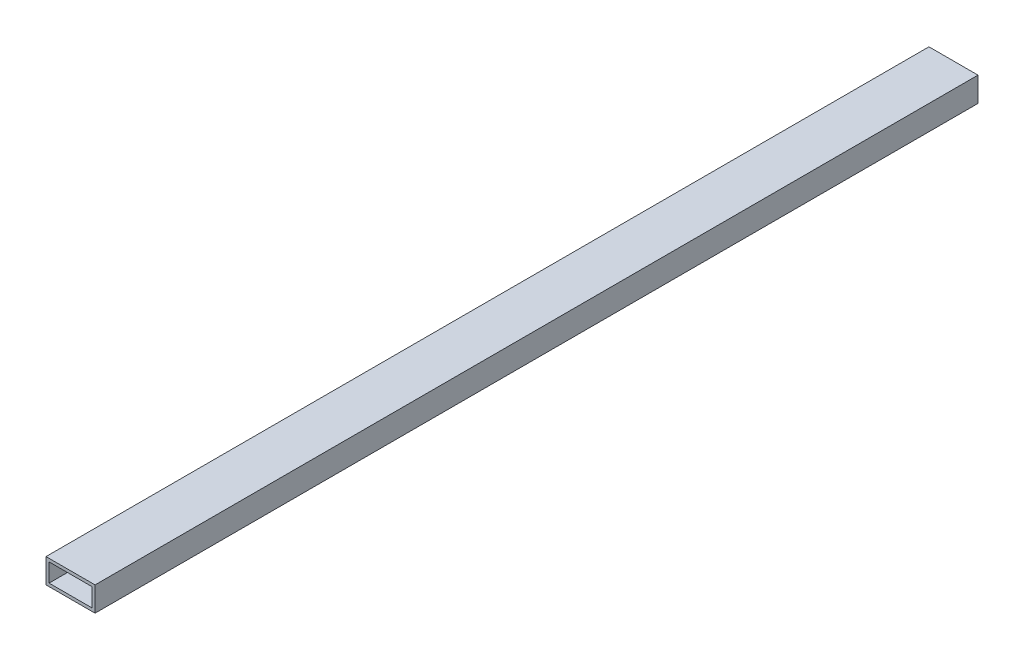
SolidWorks part; units mm, degrees
ref_plane "Front Plane" through (0, 0, 0) normal (0, 0, 1) x (1, 0, 0)
ref_plane "Top Plane" through (0, 0, 0) normal (0, 1, 0) x (1, 0, 0)
ref_plane "Right Plane" through (0, 0, 0) normal (1, 0, 0) x (0, 0, -1)
sketch "Sketch1" plane through (0, 0, 0) normal (0, 0, 1) x (1, 0, 0)
  line L0 (-22.225, 9.525) -> (22.225, 9.525)
  line L2 (-25.4, 12.7) -> (25.4, 12.7)
  line L3 (-25.4, 12.7) -> (-25.4, -12.7)
  line L4 (-25.4, -12.7) -> (25.4, -12.7)
  line L5 (25.4, 12.7) -> (25.4, -12.7)
  line L10 (22.225, 9.525) -> (22.225, -9.525)
  line L11 (-22.225, -9.525) -> (22.225, -9.525)
  line L12 (-22.225, 9.525) -> (-22.225, -9.525)
  point P12 (0, 12.7)
  point P14 (25.4, 0)
  dimension "Wall Thickness" = 3.175
  dimension "Outside Width" = 50.8
  dimension "Outside Height" = 25.4
  dimension "Inside Height" = 19.05
  dimension "Inside Width" = 44.45
sketch "Sketch2" plane through (0, 0, 0) normal (1, 0, 0) x (0, 0, -1)
  line L0 (457.2, 0) -> (-457.2, 0)
  point P4 (0, 0)
  point P7 (-457.2, 0)
  point P10 (457.2, 0)
  dimension "Length" = 914.4
sketch "Sketch3" plane through (0, 0, 0) normal (0, 0, 1) x (1, 0, 0)
  line L21 (25.4, 12.7) -> (-25.4, 12.7)
  line L22 (25.4, -12.7) -> (25.4, 12.7)
  line L23 (-25.4, -12.7) -> (25.4, -12.7)
  line L24 (-25.4, 12.7) -> (-25.4, -12.7)
  line L25 (25.4, 12.7) -> (-25.4, 12.7)
  line L26 (25.4, -12.7) -> (25.4, 12.7)
  line L27 (-25.4, -12.7) -> (25.4, -12.7)
  line L28 (-25.4, 12.7) -> (-25.4, -12.7)
  line L29 (22.225, 9.525) -> (-22.225, 9.525)
  line L30 (22.225, -9.525) -> (22.225, 9.525)
  line L31 (-22.225, -9.525) -> (22.225, -9.525)
  line L32 (-22.225, 9.525) -> (-22.225, -9.525)
  line L33 (22.225, 9.525) -> (-22.225, 9.525)
  line L34 (22.225, -9.525) -> (22.225, 9.525)
  line L35 (-22.225, -9.525) -> (22.225, -9.525)
  line L36 (-22.225, 9.525) -> (-22.225, -9.525)
  dimension "D1" = 0
  dimension "D2" = 0
extrude "Boss-Extrude1" add sketch "Sketch3" along normal up to vertex (457.2 mm away) and the other way up to vertex (457.2 mm away) up to point (0, 0, 457.2) other way up to point (0, 0, -457.2)
sketch "Drawing Reference" plane through (0, 0, 0) normal (1, 0, 0) x (0, 0, -1)
  line L0 (-457.2, 0) -> (457.2, 0) construction
  line L1 (0, -12.7) -> (0, 12.7) construction
  line L2 (-457.2, -12.7) -> (457.2, -12.7) construction
  line L5 (-457.2, 12.7) -> (457.2, 12.7) construction
  point P7 (-420.624, 0)
  point P8 (420.624, 0)
  dimension "D1" = 36.576
equation "\"D1@Drawing Reference\"=\"Outside Width@Sketch1\" * 0.72"
